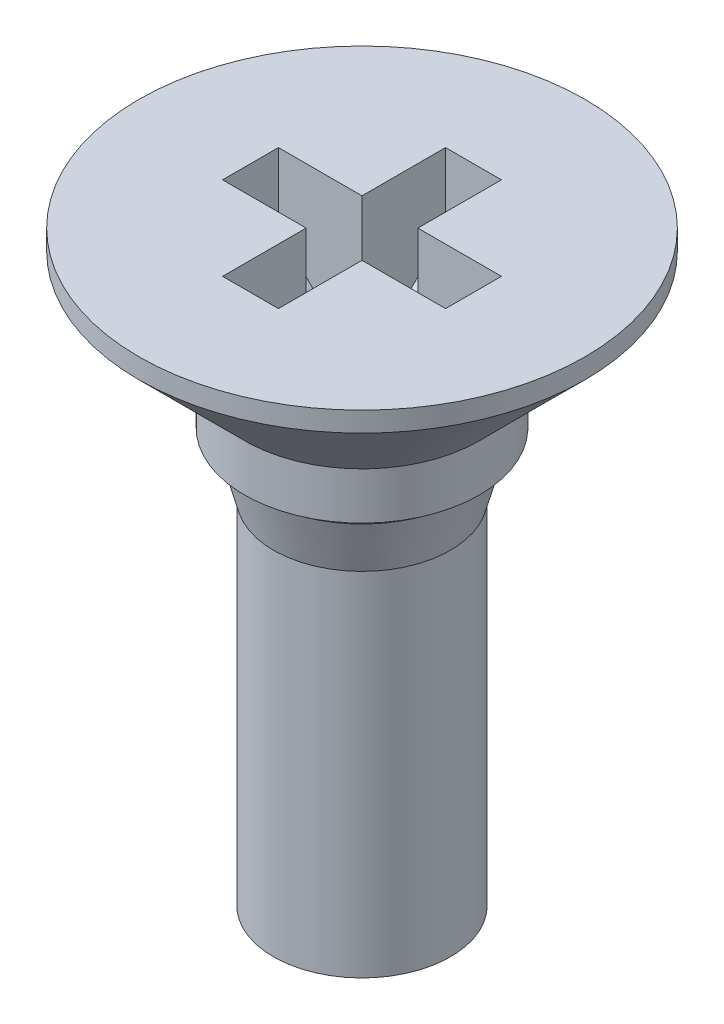
SolidWorks part; units mm, degrees
ref_plane "Vorderseite" through (0, 0, 0) normal (0, 0, 1) x (1, 0, 0)
ref_plane "Oben" through (0, 0, 0) normal (0, 1, 0) x (1, 0, 0)
ref_plane "Rechts" through (0, 0, 0) normal (1, 0, 0) x (0, 0, -1)
sketch "Skizze1" plane through (0, 0, 0) normal (0, 0, 1) x (1, 0, 0)
  line L0 (0, 0) -> (1.9, 0)
  line L1 (1.9, 0) -> (1.9, -0.17)
  line L2 (1.9, -0.17) -> (1, -1.07)
  line L3 (0.87, -1.47) -> (0.87, -1.5689)
  line L4 (0.87, -1.5689) -> (0.7545, -2)
  line L5 (0.7545, -2) -> (0.7545, -5)
  line L6 (0.7545, -5) -> (0, -5)
  line L7 (0, 0) -> (0, -5) construction
  line L8 (0, 0) -> (0, -5)
  line L10 (1, -1.07) -> (1, -1.47)
  line L12 (1, -1.47) -> (0.87, -1.47)
  point P3 (0.87, -1.2)
  dimension "D1" = 45
  dimension "D2" = 15
  dimension "K" = 1.2
  dimension "D3" = 5
  dimension "DA" = 3.8
  dimension "DK" = 1.509
  dimension "DG" = 2
  dimension "A" = 0.8
  dimension "DF" = 1.74
  dimension "P" = 0.4
revolve "Basis-Rotation" add sketch "Skizze1" angle 360 about L7
sketch "Skizze2" plane through (0, 0, 0) normal (0, 0, 1) x (1, 0, 0)
  line L0 (0, -1.2) -> (0, 0) construction
  line L1 (0, 0) -> (0, -5) construction
  line L2 (-0.35, -1.2) -> (0.35, -1.2)
  line L3 (0.95, 0) -> (0.95, -0.6)
  line L4 (0.95, -0.6) -> (0.35, -1.2)
  line L5 (0.95, 0) -> (-0.95, 0)
  line L6 (-0.95, -0.6) -> (-0.35, -1.2)
  line L7 (-0.95, 0) -> (-0.95, -0.6)
  line L8 (0, -0.6) -> (0.95, -0.6) construction
  line L9 (1.9, 0) -> (-1.9, 0) construction
  line L11 (1, -1.07) -> (1.9, -0.17) construction
  point P11 (0, 0)
  dimension "M" = 1.9
  dimension "T" = 1.2
extrude "Kreuzschlitz1 H" cut sketch "Skizze2" against normal blind 0.238 and the other way blind 0.238
sketch "Skizze3" plane through (0, 0, 0) normal (1, 0, 0) x (0, 0, -1)
  line L0 (0, -1.2) -> (0, 0) construction
  line L2 (-0.35, -1.2) -> (0.35, -1.2)
  line L3 (0.95, 0) -> (0.95, -0.6)
  line L4 (0.95, -0.6) -> (0.35, -1.2)
  line L5 (0.95, 0) -> (-0.95, 0)
  line L6 (-0.95, -0.6) -> (-0.35, -1.2)
  line L7 (-0.95, 0) -> (-0.95, -0.6)
  line L8 (0, -0.6) -> (0.95, -0.6) construction
  point P11 (0, 0)
extrude "Kreuzschlitz2 H" cut sketch "Skizze3" against normal blind 0.238 and the other way blind 0.238
sketch "Skizze4" plane through (2.4522, 0, -1.8507) normal (0, 1, 0) x (-1, 0, 0)
  line L0 (7.3522, 1.8507) -> (-2.4478, 1.8507) construction
  line L1 (2.4522, -3.0493) -> (2.4522, 6.7507) construction
  line L2 (-2.4478, 1.0342) -> (-2.4478, 2.6672)
  line L3 (-2.4478, 1.0342) -> (0.0059, 1.0342)
  line L4 (0.0059, 1.0342) -> (0.8191, 0.6258)
  line L5 (1.2273, 0.2176) -> (-1.0126, -1.6141)
  line L6 (0.8191, 0.6258) -> (-1.0126, -1.6141)
  line L7 (1.6357, -0.5956) -> (1.2273, 0.2176)
  line L8 (1.6357, -3.0493) -> (1.6357, -0.5956)
  line L9 (1.6357, -3.0493) -> (3.2687, -3.0493)
  line L10 (3.2687, -3.0493) -> (3.2687, -0.5956)
  line L11 (3.2687, -0.5956) -> (3.6772, 0.2176)
  line L12 (2.4522, 1.8507) -> (-1.0126, -1.6141) construction
  line L13 (4.0854, 0.6258) -> (5.917, -1.6141)
  line L14 (3.6772, 0.2176) -> (5.917, -1.6141)
  line L15 (4.8986, 1.0342) -> (4.0854, 0.6258)
  line L16 (7.3522, 1.0342) -> (4.8986, 1.0342)
  line L17 (7.3522, 1.0342) -> (7.3522, 2.6672)
  line L18 (7.3522, 2.6672) -> (4.8986, 2.6672)
  line L19 (4.8986, 2.6672) -> (4.0854, 3.0757)
  line L20 (3.6772, 3.4839) -> (5.917, 5.3156)
  line L21 (4.0854, 3.0757) -> (5.917, 5.3156)
  line L22 (3.2687, 4.2971) -> (3.6772, 3.4839)
  line L23 (3.2687, 6.7507) -> (3.2687, 4.2971)
  line L24 (1.6357, 6.7507) -> (3.2687, 6.7507)
  line L25 (1.6357, 6.7507) -> (1.6357, 4.2971)
  line L26 (1.6357, 4.2971) -> (1.2273, 3.4839)
  line L27 (0.8191, 3.0757) -> (-1.0126, 5.3156)
  line L28 (1.2273, 3.4839) -> (-1.0126, 5.3156)
  line L29 (0.0059, 2.6672) -> (0.8191, 3.0757)
  line L30 (-2.4478, 2.6672) -> (0.0059, 2.6672)
  circle A0 centre (2.4522, 1.8507) radius 4.9 construction
  circle A1 centre (2.4522, 1.8507) radius 2.0415 construction
  circle A2 centre (2.4522, 1.8507) radius 2.579 construction
  dimension "X2" = 4.083
  dimension "X1" = 5.158
  dimension "M" = 9.8
  dimension "D3" = 5.725
  dimension "X3" = 1.633
